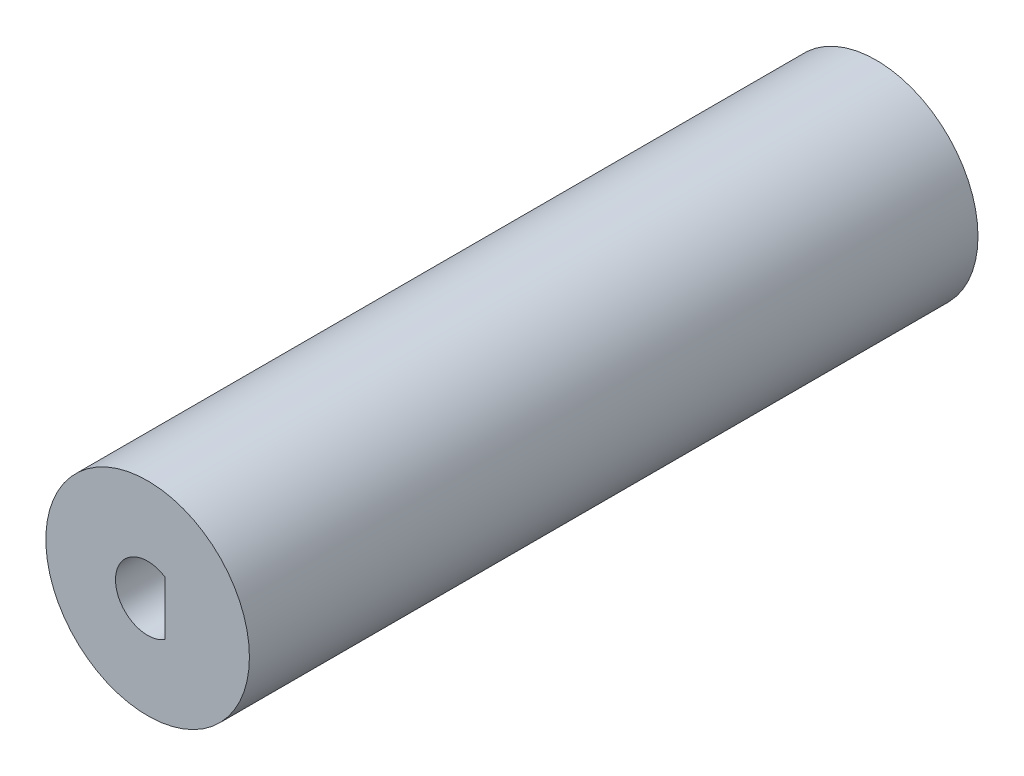
SolidWorks part; units mm, degrees
ref_plane "前视基准面" through (0, 0, 0) normal (0, 0, 1) x (1, 0, 0)
ref_plane "上视基准面" through (0, 0, 0) normal (0, 1, 0) x (1, 0, 0)
ref_plane "右视基准面" through (0, 0, 0) normal (1, 0, 0) x (0, 0, -1)
sketch "草图1" plane through (0, 0, 0) normal (0, 0, 1) x (1, 0, 0)
  circle A0 centre (0, 0) radius 4.75
extrude "凸台-拉伸1" add sketch "草图1" against normal blind 33.5 and the other way blind 0.5
sketch "草图2" plane through (0, 0, -33.5) normal (0, 0, -1) x (-1, 0, 0)
  circle A0 centre (0, 0) radius 1.5
  dimension "D1" = 3
extrude "切除-拉伸1" cut sketch "草图2" against normal blind 10
sketch "草图3" plane through (0, 0, 0.5) normal (0, 0, 1) x (1, 0, 0)
  line L0 (0.8, 1.2689) -> (0.8, -1.2689)
  arc A0 (0.8, 1.2689) -> (0.8, -1.2689) centre (0, 0) ccw
  dimension "D1" = 3
  dimension "D2" = 0.8
extrude "切除-拉伸2" cut sketch "草图3" against normal blind 8
